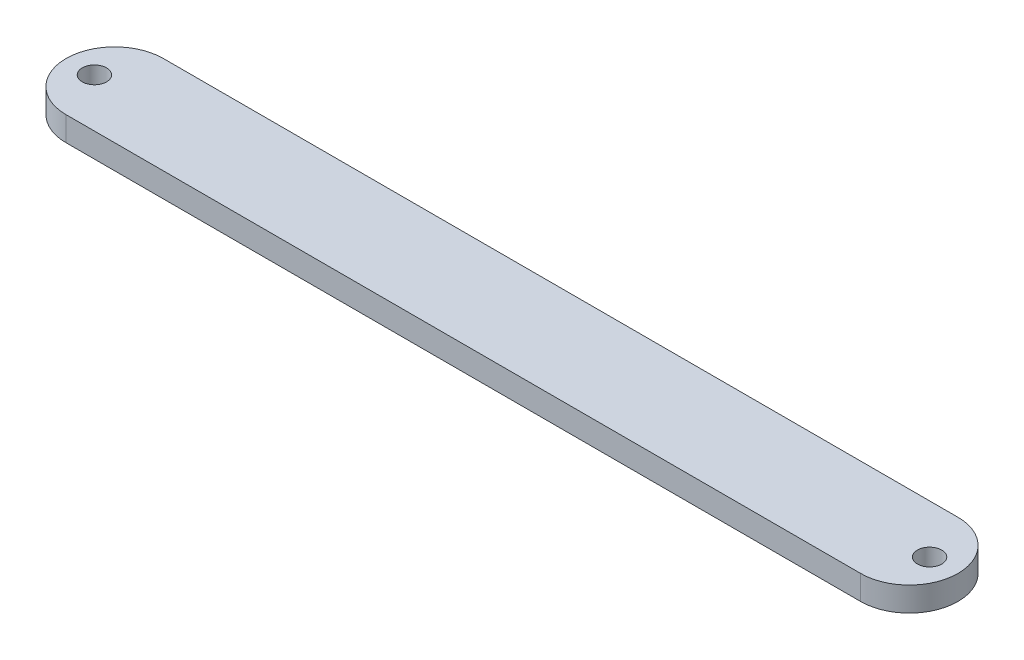
SolidWorks part; units mm, degrees
ref_plane "Front Plane" through (0, 0, 0) normal (0, 0, 1) x (1, 0, 0)
ref_plane "Top Plane" through (0, 0, 0) normal (0, 1, 0) x (1, 0, 0)
ref_plane "Right Plane" through (0, 0, 0) normal (1, 0, 0) x (0, 0, -1)
sketch "Sketch1" plane through (0, 0, 0) normal (0, 1, 0) x (1, 0, 0)
  line L0 (-49, 0) -> (49, 0) construction
  line L1 (-49, 6) -> (49, 6)
  line L2 (-49, -6) -> (49, -6)
  arc A0 (-49, 6) -> (-49, -6) centre (-49, 0) ccw
  arc A1 (49, -6) -> (49, 6) centre (49, 0) ccw
  circle A2 centre (-51.5, 0) radius 1.5
  circle A3 centre (51.5, 0) radius 1.5
  point P2 (0, 0)
  point P12 (-55, 0)
  point P13 (55, 0)
  point P14 (0, 0)
  point P15 (0, 0)
  point P16 (-51.6771, 0)
  dimension "D3" = 3
  dimension "D4" = 3.5
  dimension "D1" = 110
  dimension "D2" = 12
  dimension "D5" = 3.5
extrude "Boss-Extrude1" add sketch "Sketch1" along normal blind 3 contours L2 A1 L1 A0 | A2 | A3
